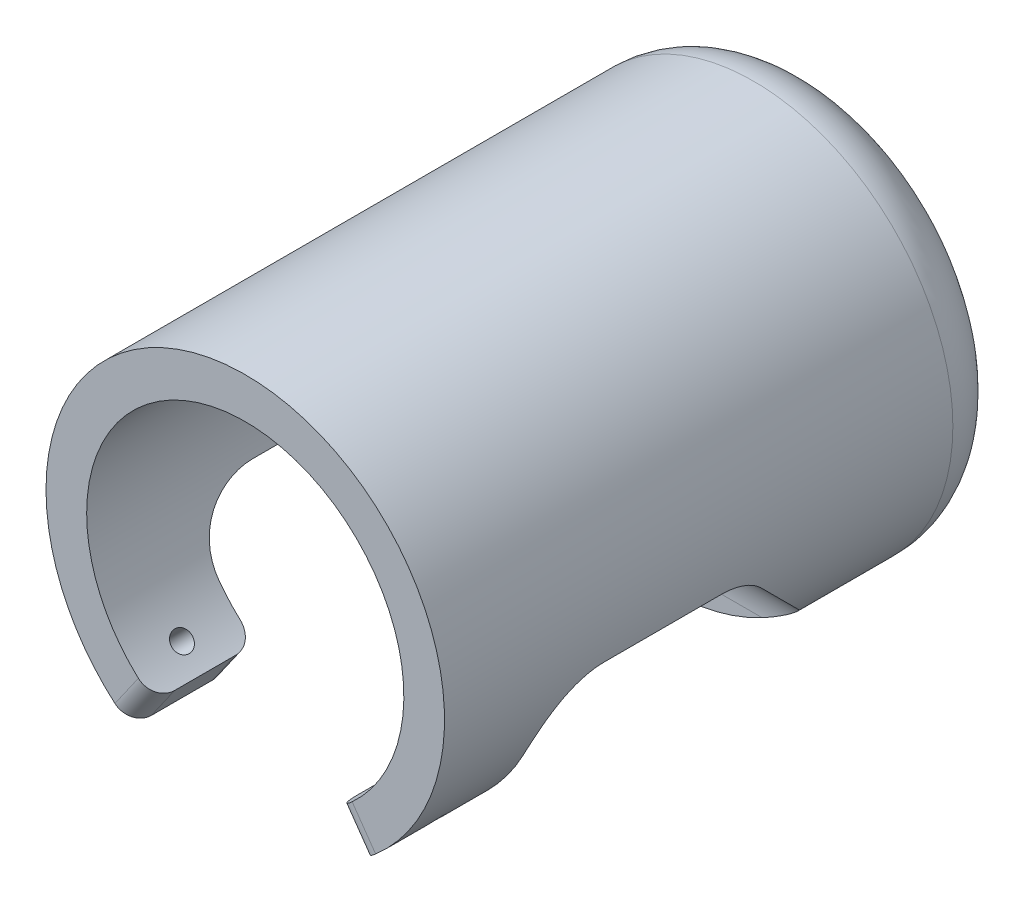
SolidWorks part; units mm, degrees
material "硅橡胶板 "
ref_plane "前视" through (0, 0, 0) normal (0, 0, 1) x (1, 0, 0)
ref_plane "上视" through (0, 0, 0) normal (0, 1, 0) x (1, 0, 0)
ref_plane "右视" through (0, 0, 0) normal (1, 0, 0) x (0, 0, -1)
sketch "草图1" plane through (0, 0, 0) normal (0, 0, 1) x (1, 0, 0)
  circle A0 centre (0, 0) radius 49
  circle A1 centre (0, 0) radius 46 construction
  dimension "D1" = 98
  dimension "D2" = 3
extrude "凸台-拉伸1" add sketch "草图1" along normal mid plane 140
fillet "圆角1" radius 15 1 edges at (49, 0, -70)
shell "抽壳1" thickness 10
sketch "草图2" plane through (0, 0, 0) normal (1, 0, 0) x (0, 0, -1)
  line L0 (0, 0) -> (-70.7678, 0) construction
  line L1 (-45, -49) -> (-45, -23)
  line L2 (-70, -49) -> (55, -49) construction
  line L3 (-30, -8) -> (-1.2132, -8)
  line L5 (-70, 49) -> (-70, -49) construction
  line L6 (-45, -49) -> (34, -49)
  line L7 (34, -49) -> (34, -43.2132)
  line L8 (29.6066, -32.6066) -> (9.3934, -12.3934)
  line L9 (70, -34) -> (70, 34) construction
  arc A1 (-45, -23) -> (-30, -8) centre (-30, -23) cw
  arc A2 (-1.2132, -8) -> (9.3934, -12.3934) centre (-1.2132, -23) cw
  arc A3 (34, -43.2132) -> (29.6066, -32.6066) centre (19, -43.2132) ccw
  point P12 (5, -8)
  point P13 (5, -8)
  point P16 (-45, -8)
  point P20 (-45, -8)
  point P22 (34, -37)
  dimension "D5" = 45
  dimension "D6" = 15
  dimension "D8" = 15
  dimension "D1" = 25
  dimension "D2" = 8
  dimension "D3" = 36
  dimension "D4" = 12
  dimension "D7" = 0
extrude "切除-拉伸1" cut sketch "草图2" against normal through all both and the other way through all
sketch "草图3" plane through (0, 0, 70) normal (0, 0, 1) x (1, 0, 0)
  line L0 (0, 0) -> (0, -75.8405) construction
  line L1 (22.3695, -31.9469) -> (28.1052, -40.1385)
  line L2 (-22.3695, -31.9469) -> (-28.1052, -40.1385)
  circle A0 centre (0, 0) radius 49 construction
  circle A1 centre (0, 0) radius 39 construction
  arc A2 (-28.1052, -40.1385) -> (28.1052, -40.1385) centre (0, 0) ccw
  arc A3 (-22.3695, -31.9469) -> (22.3695, -31.9469) centre (0, 0) ccw
  dimension "D1" = 70
extrude "切除-拉伸2" cut sketch "草图3" against normal up to next
sketch "草图4" plane through (0, 0, 70) normal (0, 0, 1) x (1, 0, 0)
  circle A0 centre (0, 0) radius 30
  dimension "D1" = 60
extrude "切除-拉伸3" cut sketch "草图4" against normal through all
fillet "圆角2" radius 5 4 edges at (-25.2374, -36.0427, 45) (-25.2374, -36.0427, 70) (25.2374, -36.0427, 70) (25.2374, -36.0427, 45)
ref_plane "基准面2" through (0, 0, 58) normal (0, 0, 1) x (1, 0, 0)
sketch "草图6" plane through (0, 0, 58) normal (0, 0, 1) x (1, 0, 0)
  line L0 (0, -69.3583) -> (0, 0) construction
  line L1 (0, 0) -> (65.9954, -65.9954) construction
  line L2 (0, 0) -> (1.7678, 1.7678)
  line L3 (1.7678, 1.7678) -> (56.3134, -52.7779)
  line L4 (56.3134, -52.7779) -> (54.5457, -54.5457)
  line L5 (54.5457, -54.5457) -> (0, 0)
  dimension "D1" = 45
  dimension "D2" = 5
revolve "切除-旋转1" cut sketch "草图6" angle 360 about L1
mirror "镜向2" about plane through (0, 0, 0) normal (1, 0, 0) of "切除-旋转1"
